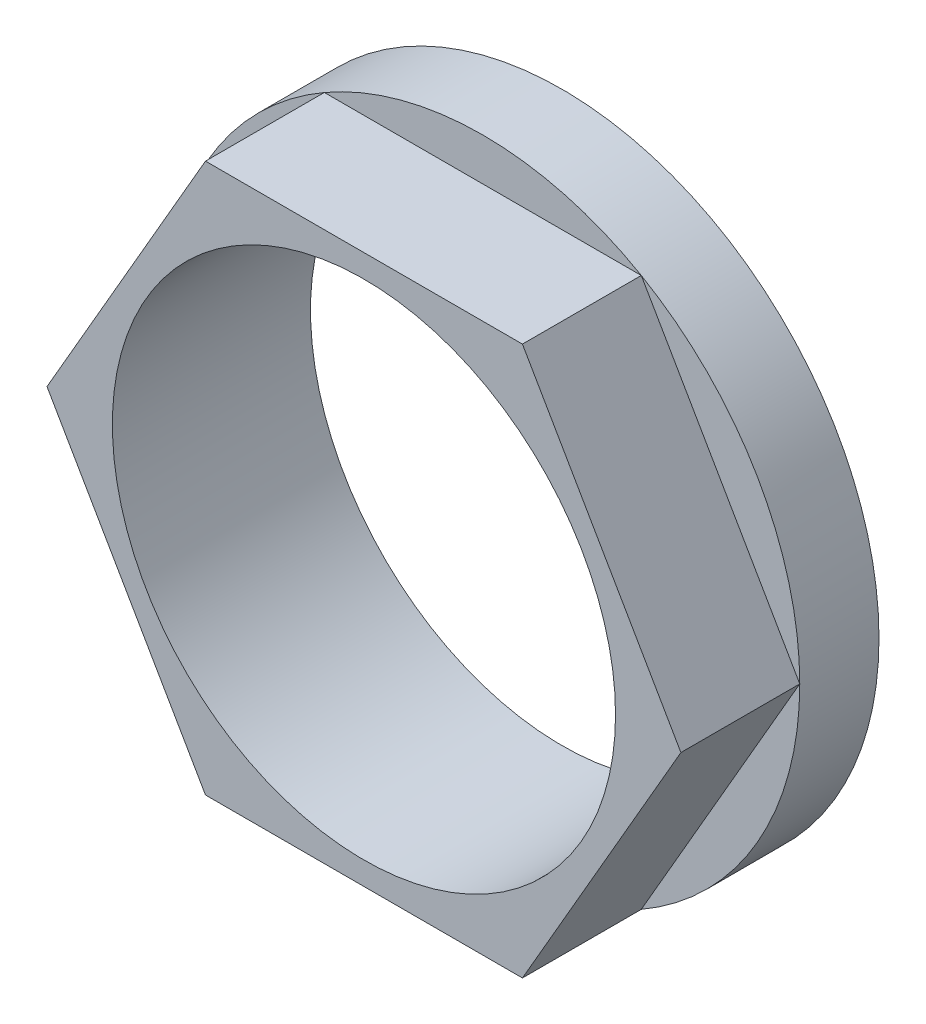
SolidWorks part; units mm, degrees
ref_plane "Plan de face" through (0, 0, 0) normal (0, 0, 1) x (1, 0, 0)
ref_plane "Plan de dessus" through (0, 0, 0) normal (0, 1, 0) x (1, 0, 0)
ref_plane "Plan de droite" through (0, 0, 0) normal (1, 0, 0) x (0, 0, -1)
sketch "Esquisse1" plane through (0, 0, 0) normal (0, 0, 1) x (1, 0, 0)
  circle A0 centre (0, 0) radius 8
  circle A1 centre (0, 0) radius 6.35
  dimension "D1" = 12.7
  dimension "D2" = 16
extrude "Boss.-Extru.1" add sketch "Esquisse1" along normal blind 2
sketch "Esquisse2" plane through (0, 0, 2) normal (0, 0, 1) x (1, 0, 0)
  line L1 (8, 0) -> (4, 6.9282)
  line L2 (4, 6.9282) -> (-4, 6.9282)
  line L3 (-4, 6.9282) -> (-8, 0)
  line L4 (-8, 0) -> (-4, -6.9282)
  line L5 (-4, -6.9282) -> (4, -6.9282)
  line L6 (4, -6.9282) -> (8, 0)
  circle A0 centre (0, 0) radius 6.9282 construction
  circle A1 centre (0, 0) radius 6.35 construction
  circle A2 centre (0, 0) radius 6.35
extrude "Boss.-Extru.2" add sketch "Esquisse2" along normal blind 3
